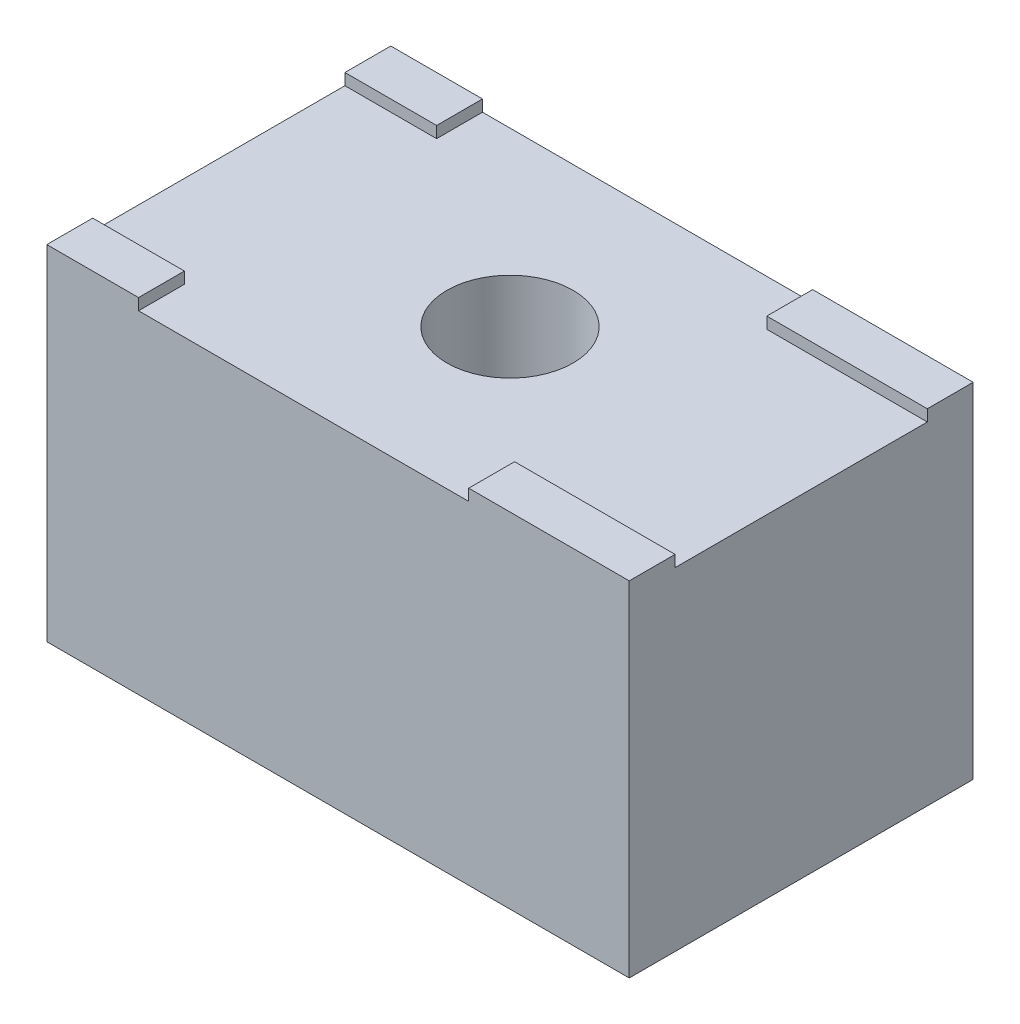
SolidWorks part; units mm, degrees
ref_plane "Front Plane" through (0, 0, 0) normal (0, 0, 1) x (1, 0, 0)
ref_plane "Top Plane" through (0, 0, 0) normal (0, 1, 0) x (1, 0, 0)
ref_plane "Right Plane" through (0, 0, 0) normal (1, 0, 0) x (0, 0, -1)
sketch "Sketch1" plane through (0, 0, 0) normal (1, 0, 0) x (0, 0, -1)
  line L1 (-7.5, 7.5) -> (7.5, 7.5)
  line L2 (-7.5, 7.5) -> (-7.5, -7.5)
  line L3 (-7.5, -7.5) -> (7.5, -7.5)
  line L4 (7.5, 7.5) -> (7.5, -7.5)
  line L5 (-7.5, 7.5) -> (7.5, -7.5) construction
  line L6 (-7.5, -7.5) -> (7.5, 7.5) construction
  point P0 (0, 0)
  dimension "D1" = 15
  dimension "D2" = 15
extrude "Boss-Extrude1" add sketch "Sketch1" along normal blind 25.4
sketch "Sketch2" plane through (0, 7.5, 0) normal (0, 1, 0) x (1, 0, 0)
  line L0 (0, 7.5) -> (0, -7.5) construction
  circle A0 centre (12.7, 0) radius 2.75
  point P6 (0, 0)
  dimension "D1" = 5.5
  dimension "D2" = 12.7
extrude "Cut-Extrude1" cut sketch "Sketch2" against normal through all
sketch "Sketch3" plane through (0, 0, -7.5) normal (0, 0, -1) x (-1, 0, 0)
  line L0 (0, -7.5) -> (0, 7.5) construction
  line L1 (0, 3.5) -> (-10, 3.5)
  line L2 (0, 3.5) -> (0, -3.358)
  line L3 (0, -3.358) -> (-10, -3.358)
  line L4 (-10, 3.5) -> (-10, -3.358)
  line L5 (-10, 0.071) -> (-4.92, 0.071) construction
  line L6 (-25.4, 7.5) -> (0, 7.5) construction
  circle A0 centre (-4.92, 0.071) radius 1.5875
  dimension "D2" = 3.175
  dimension "D1" = 6.858
  dimension "D3" = 5.08
  dimension "D4" = 10
  dimension "D5" = 4
extrude "Cut-Extrude2" cut sketch "Sketch3" against normal blind 1.778
fillet "Fillet1" radius 0.7937 2 edges at (10, 3.5, -6.611) (10, -3.358, -6.611)
sketch "Sketch5" plane through (0, 0, -7.5) normal (0, 0, -1) x (-1, 0, 0)
  line L0 (0, -7.5) -> (0, -3.358)
  line L1 (0, -7.5) -> (-3.9016, -7.5)
  line L2 (-25.4, -7.5) -> (0, -7.5) construction
sketch "Sketch6" plane through (0, 7.5, 0) normal (0, 1, 0) x (1, 0, 0)
  text T0 "Top"
sketch "Sketch7" plane through (0, 7.5, 0) normal (0, 1, 0) x (1, 0, 0)
  line L0 (25.4, 7.5) -> (0, 7.5) construction
  line L1 (4, 7.5) -> (18.4, 7.5)
  line L2 (4, 7.5) -> (4, 5.5)
  line L3 (4, -7.5) -> (18.4, -7.5)
  line L4 (18.4, 7.5) -> (18.4, 5.5)
  line L5 (25.4, -7.5) -> (0, -7.5) construction
  line L6 (25.4, 7.5) -> (25.4, -7.5) construction
  line L7 (0, 7.5) -> (0, -7.5) construction
  line L8 (0, 7.5) -> (3.9016, 7.5) construction
  line L9 (18.4, 5.5) -> (25.4, 5.5)
  line L11 (18.4, -5.5) -> (25.4, -5.5)
  line L12 (25.4, 5.5) -> (25.4, -5.5)
  line L13 (4, 5.5) -> (0, 5.5)
  line L14 (18.4, -5.5) -> (18.4, -7.5)
  line L15 (4, -5.5) -> (0, -5.5)
  line L16 (0, 5.5) -> (0, -5.5)
  line L17 (4, -5.5) -> (4, -7.5)
  point P20 (0, 0)
  point P21 (25.4, 0)
  dimension "D1" = 7
  dimension "D2" = 4
  dimension "D3" = 2
  dimension "D4" = 2
extrude "Cut-Extrude3" cut sketch "Sketch7" against normal blind 0.5
sketch "Rough Stock" plane through (0, 0, 0) normal (1, 0, 0) x (0, 0, -1)
  line L0 (-8.7165, 8.0264) -> (-10.16, -8.0264)
  line L1 (10.16, -8.0264) -> (-10.16, -8.0264)
  line L3 (9.2465, 8.0264) -> (-8.7165, 8.0264)
  line L5 (10.16, -8.0264) -> (-8.8122, 6.9617) construction
  line L6 (9.2858, 7.3358) -> (-10.16, -8.0264) construction
  line L7 (10.16, -8.0264) -> (9.2465, 8.0264)
  point P0 (0, 0)
  dimension "D1" = 16.0528
  dimension "D2" = 20.32
sketch "Sketch9" plane through (0, 0, 0) normal (-1, 0, 0) x (0, 0, 1)
  line L8 (-5.722, 3.5) -> (-5.722, -3.358)
  line L9 (-5.722, -3.358) -> (-7.5, -3.358)
  line L10 (-7.5, -3.358) -> (-7.5, -7.5)
  line L11 (-7.5, -7.5) -> (7.5, -7.5)
  line L12 (7.5, -7.5) -> (7.5, 7.5)
  line L13 (7.5, 7.5) -> (5.5, 7.5)
  line L14 (-7.5, 7.5) -> (-7.5, 3.5)
  line L15 (-7.5, 3.5) -> (-5.722, 3.5)
  line L16 (-5.722, 3.5) -> (-5.722, -3.358)
  line L17 (-5.722, -3.358) -> (-7.5, -3.358)
  line L18 (-7.5, -3.358) -> (-7.5, -7.5)
  line L19 (-7.5, -7.5) -> (7.5, -7.5)
  line L20 (7.5, -7.5) -> (7.5, 7.5)
  line L21 (7.5, 7.5) -> (5.5, 7.5)
  line L22 (-7.5, 7.5) -> (-7.5, 3.5)
  line L23 (-7.5, 3.5) -> (-5.722, 3.5)
  line L29 (5.5, 7.5) -> (5.5, 7)
  line L30 (5.5, 7.5) -> (5.5, 7)
  line L31 (5.5, 7) -> (-5.5, 7)
  line L32 (5.5, 7) -> (-5.5, 7)
  line L33 (-5.5, 7) -> (-5.5, 7.5)
  line L34 (-5.5, 7) -> (-5.5, 7.5)
  line L35 (-5.5, 7.5) -> (-7.5, 7.5)
  line L36 (-5.5, 7.5) -> (-7.5, 7.5)
  dimension "D1" = 0
